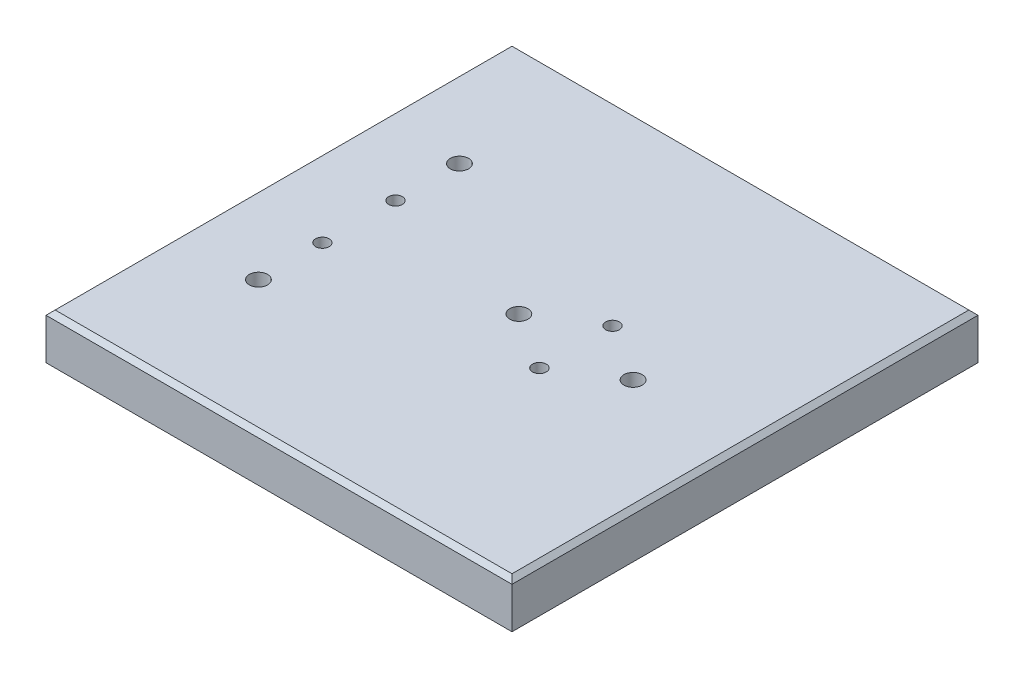
SolidWorks part; units mm, degrees
ref_plane "Ön Düzlem" through (0, 0, 0) normal (0, 0, 1) x (1, 0, 0)
ref_plane "Üst Düzlem" through (0, 0, 0) normal (0, 1, 0) x (1, 0, 0)
ref_plane "Sağ Düzlem" through (0, 0, 0) normal (1, 0, 0) x (0, 0, -1)
sketch "Çizim1" plane through (0, 0, 0) normal (0, 1, 0) x (1, 0, 0)
  line L1 (-51, -51) -> (51, -51)
  line L2 (-51, -51) -> (-51, 51)
  line L3 (-51, 51) -> (51, 51)
  line L4 (51, -51) -> (51, 51)
  line L5 (-51, -51) -> (51, 51) construction
  line L6 (-51, 51) -> (51, -51) construction
  point P0 (0, 0)
  dimension "D1" = 102
  dimension "D3" = 102
extrude "Yükseklik-Ekstrüzyon1" add sketch "Çizim1" along normal blind 10
sketch "Çizim4" plane through (-51, 0, 0) normal (-1, 0, 0) x (0, 0, 1)
  line L0 (-51, 0) -> (51, 0) construction
  circle A0 centre (-8, 5) radius 2.5
  circle A1 centre (8, 5) radius 2.5
  dimension "D1" = 5
  dimension "D4" = 5
  dimension "D2" = 8
  dimension "D3" = 8
extrude "Kes-Ekstrüzyon1" cut sketch "Çizim4" against normal blind 9.5
sketch "Çizim5" plane through (-41.5, 0, 0) normal (-1, 0, 0) x (0, 0, 1)
  circle A0 centre (-8, 5) radius 1.5
  circle A1 centre (8, 5) radius 1.5
  dimension "D1" = 3
  dimension "D2" = 3
extrude "Kes-Ekstrüzyon2" cut sketch "Çizim5" against normal blind 58
sketch "Çizim6" plane through (0, 0, 0) normal (0, -1, 0) x (-1, 0, 0)
  line L0 (78.964, 0) -> (-78.964, 0) construction
  line L1 (51, 51) -> (51, -51) construction
  line L2 (-14, 22.8316) -> (-14, -22.8316) construction
  circle A0 centre (33.5, -22) radius 3.5
  circle A1 centre (33.5, 22) radius 3.5
  circle A2 centre (-1.5, 0) radius 3.5
  circle A3 centre (-26.5, 0) radius 3.5
  point P12 (0, 0)
  point P19 (0, 0)
  dimension "D1" = 7
  dimension "D2" = 22
  dimension "D5" = 47.5
  dimension "D7" = 12.5
  dimension "D3" = 22
  dimension "D4" = 17.5
  dimension "D6" = 12.5
extrude "Kes-Ekstrüzyon9" cut sketch "Çizim6" against normal blind 5
sketch "Çizim9" plane through (0, 5, 0) normal (0, -1, 0) x (1, 0, 0)
  circle A0 centre (-33.5, 22) radius 2
  circle A1 centre (1.5, 0) radius 2
  circle A2 centre (26.5, 0) radius 2
  circle A3 centre (-33.5, -22) radius 2
  dimension "D1" = 4
extrude "Kes-Ekstrüzyon10" cut sketch "Çizim9" against normal blind 5
sketch "Çizim10" plane through (0, 10, 0) normal (0, 1, 0) x (1, 0, 0)
  line L0 (-33.5, -38.6491) -> (-33.5, 33.7858) construction
  line L1 (1.5, 0) -> (-47.2832, 0) construction
  line L2 (1.5, 0) -> (26.5, 0) construction
  line L3 (26.5, 0) -> (46.6702, 0) construction
  circle A0 centre (-33.5, 8) radius 1.5
  circle A1 centre (-33.5, -8) radius 1.5
  circle A2 centre (14, 8) radius 1.5
  circle A3 centre (14, -8) radius 1.5
  point P0 (-33.5, 22)
  dimension "D1" = 8
  dimension "D2" = 3
  dimension "D3" = 47.5
extrude "Kes-Ekstrüzyon18" cut sketch "Çizim10" against normal blind 8
chamfer "Pah1" distance 1 angle 45 4 edges at (-51, 10, 0) (0, 10, -51) (51, 10, 0) (0, 10, 51)
